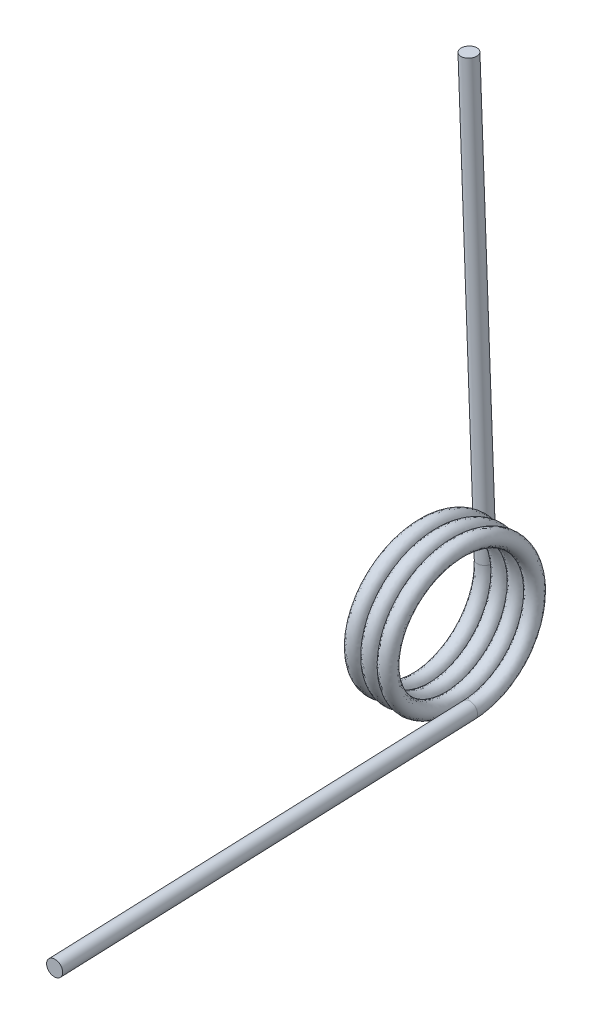
SolidWorks part; units mm, degrees
ref_plane "Front" through (0, 0, 0) normal (0, 0, 1) x (1, 0, 0)
ref_plane "Top" through (0, 0, 0) normal (0, 1, 0) x (1, 0, 0)
ref_plane "Right" through (0, 0, 0) normal (1, 0, 0) x (0, 0, -1)
sketch "Sketch1" plane through (0, 0, 0) normal (1, 0, 0) x (0, 0, -1)
  line L0 (0, 0) -> (0, -1.8034) construction
  line L1 (0, -1.8034) -> (0, -2.032) construction
  line L2 (0, -2.032) -> (0, -2.2606) construction
  circle A0 centre (0, 0) radius 1.8034 construction
  circle A1 centre (0, 0) radius 2.2606 construction
  circle A2 centre (0, 0) radius 2.032
  circle A3 centre (0, -2.032) radius 0.2286 construction
  circle A4 centre (0, 0) radius 1.3843 construction
  dimension "Wire Dia" = 0.4572
  dimension "Spring OD" = 4.5212
  dimension "Max Rod OD" = 2.7686
curve "Helix/Spiral1" pitch 0.4826 height 1.5684 turns 3.25
ref_plane "Plane1" through (0, 0, -2.032) normal (0.0378, -0.9993, 0) x (0.9993, 0.0378, 0)
sketch "Sketch2" plane through (0, 0, -2.032) normal (0.0378, -0.9993, 0) x (0.9993, 0.0378, 0)
  circle A0 centre (0, 0) radius 0.2286
  dimension "D1" = 0.4572
sweep "Sweep1" add profiles "Sketch2" path "Helix/Spiral1"
sketch "Sketch3" plane through (0, 0, 0) normal (-0.0378, 0.9993, 0) x (-0.9993, -0.0378, 0)
  circle A1 centre (0, -2.032) radius 0.2286
  circle A2 centre (0, -2.032) radius 0.2286
  dimension "D1" = 0
extrude "Extrude1" add sketch "Sketch3" along normal blind 12.7
sketch "Sketch4" plane through (0.0022, 0, 0.0592) normal (0.0378, 0, 0.9993) x (0.9993, 0, -0.0378)
  circle A1 centre (1.5673, -2.032) radius 0.2286
  circle A2 centre (1.5673, -2.032) radius 0.2286
  dimension "D1" = 0
extrude "Extrude2" add sketch "Sketch4" along normal blind 12.7
sketch "Sketch5" plane through (0, 0, 0) normal (1, 0, 0) x (0, 0, -1)
  circle A0 centre (0, 0) radius 1.3843 construction
  circle A1 centre (0, 0) radius 1.3843
equation "\"D4@Helix/Spiral1\"=\"Wire Dia@Sketch1\"+.001"
equation "\"D1@Sketch2\"=\"Wire Dia@Sketch1\""
equation "\"D1@Extrude2\"=\"Leg Length@Extrude1\""
